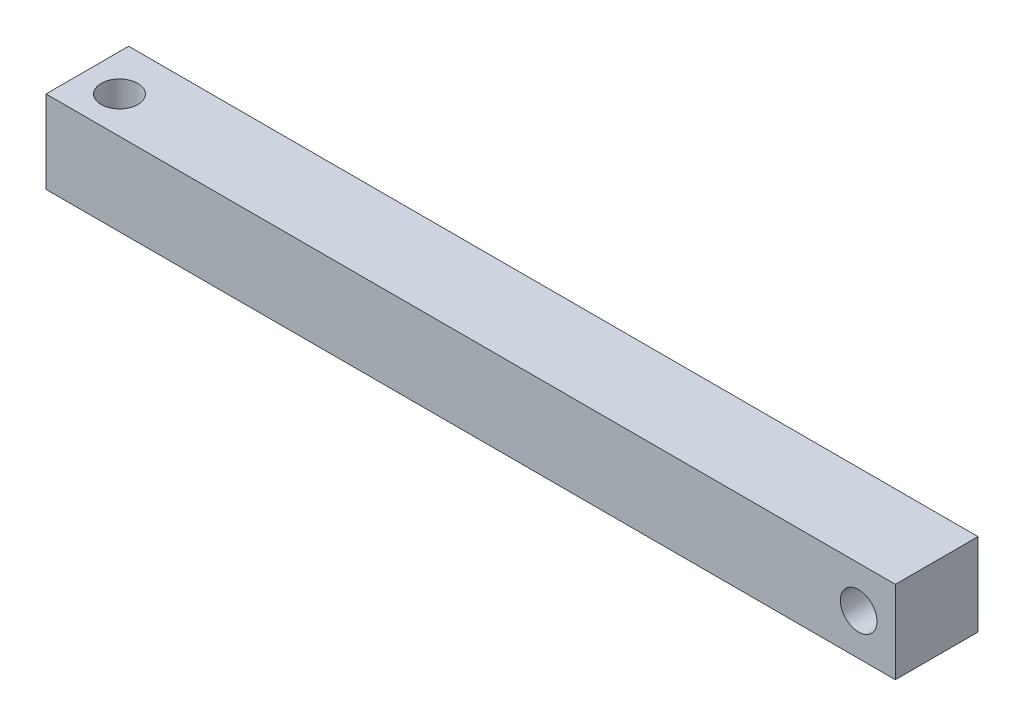
SolidWorks part; units mm, degrees
ref_plane "Front Plane" through (0, 0, 0) normal (0, 0, 1) x (1, 0, 0)
ref_plane "Top Plane" through (0, 0, 0) normal (0, 1, 0) x (1, 0, 0)
ref_plane "Right Plane" through (0, 0, 0) normal (1, 0, 0) x (0, 0, -1)
sketch "Sketch1" plane through (0, 0, 0) normal (0, 0, 1) x (1, 0, 0)
  line L1 (-41.7799, 12.0275) -> (-4.7799, 12.0275)
  line L2 (-41.7799, 12.0275) -> (-41.7799, 8.4275)
  line L3 (-41.7799, 8.4275) -> (-4.7799, 8.4275)
  line L4 (-4.7799, 12.0275) -> (-4.7799, 8.4275)
  dimension "D1" = 37
  dimension "D2" = 3.6
extrude "Boss-Extrude1" add sketch "Sketch1" along normal blind 3.6
sketch "Sketch2" plane through (0, 0, 3.6) normal (0, 0, 1) x (1, 0, 0)
  line L0 (-4.7799, 12.0275) -> (-41.7799, 12.0275) construction
  line L1 (-4.7799, 8.4275) -> (-4.7799, 12.0275) construction
  circle A0 centre (-6.3799, 10.2275) radius 0.8
  dimension "D1" = 1.6
  dimension "D2" = 1.8
  dimension "D3" = 1.6
extrude "Cut-Extrude1" cut sketch "Sketch2" against normal blind 3.6
sketch "Sketch3" plane through (0, 8.4275, 0) normal (0, -1, 0) x (1, 0, 0)
  line L0 (-41.7799, 3.6) -> (-4.7799, 3.6) construction
  line L1 (-41.7799, 3.6) -> (-41.7799, 0) construction
  circle A0 centre (-40.1799, 2) radius 0.8
  dimension "D1" = 1.6
  dimension "D2" = 1.6
  dimension "D3" = 1.6
extrude "Cut-Extrude2" cut sketch "Sketch3" against normal blind 3.6
